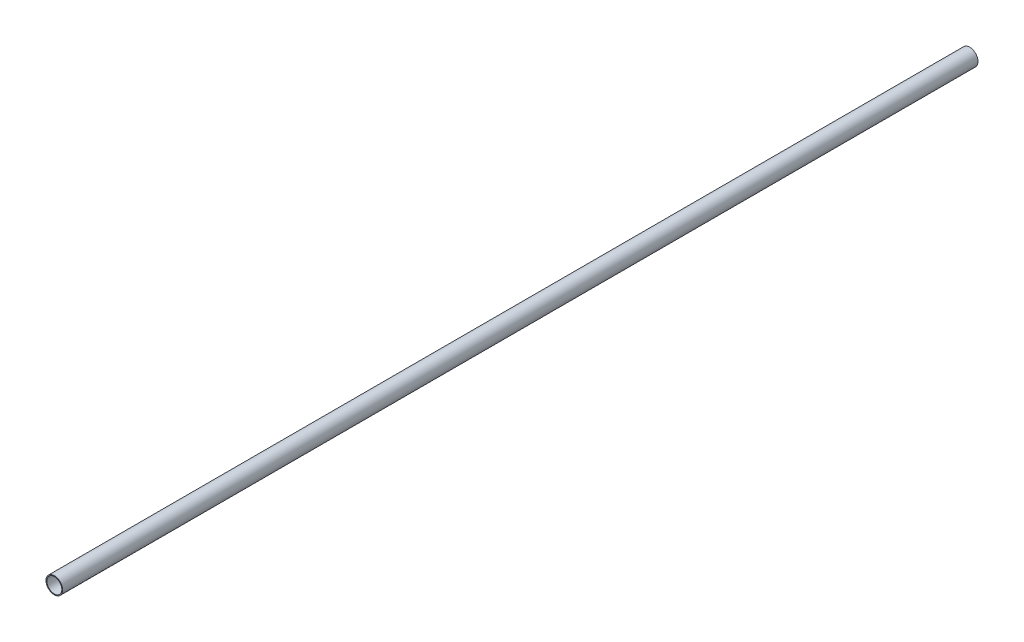
SolidWorks part; units mm, degrees
material "ABS"
ref_plane "Front Plane" through (0, 0, 0) normal (0, 0, 1) x (1, 0, 0)
ref_plane "Top Plane" through (0, 0, 0) normal (0, 1, 0) x (1, 0, 0)
ref_plane "Right Plane" through (0, 0, 0) normal (1, 0, 0) x (0, 0, -1)
sketch "Sketch1" plane through (0, 0, 0) normal (0, 0, 1) x (1, 0, 0)
  circle A0 centre (0, 0) radius 10
  circle A1 centre (0, 0) radius 9
  dimension "D1" = 1
  dimension "D2" = 20
extrude "Boss-Extrude1" add sketch "Sketch1" along normal mid plane 1100
